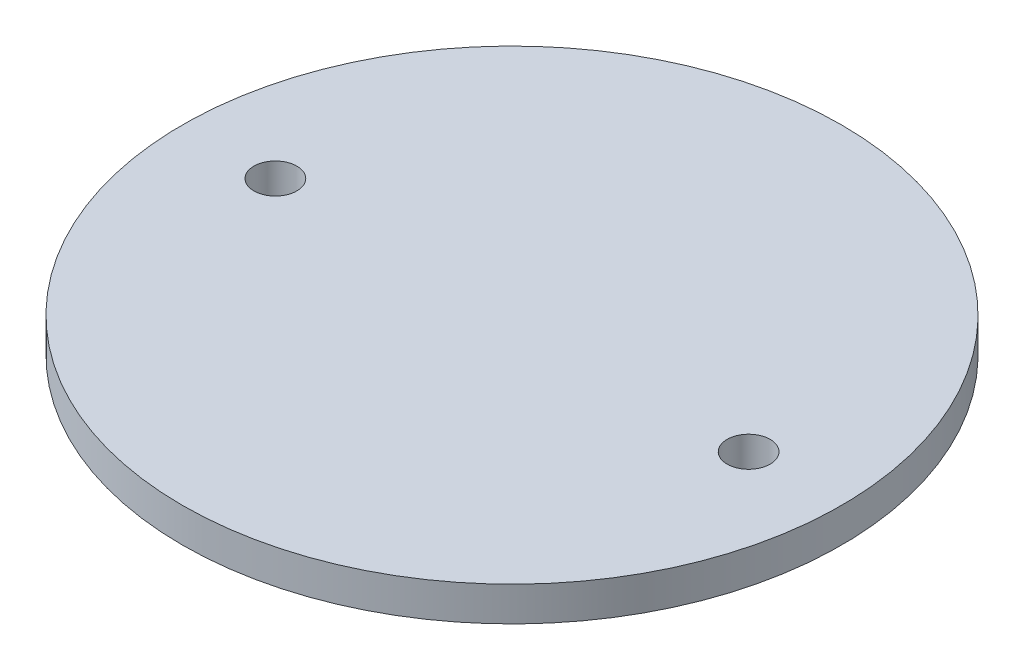
SolidWorks part; units mm, degrees
material "Balsa"
ref_plane "Front Plane" through (0, 0, 0) normal (0, 0, 1) x (1, 0, 0)
ref_plane "Top Plane" through (0, 0, 0) normal (0, 1, 0) x (1, 0, 0)
ref_plane "Right Plane" through (0, 0, 0) normal (1, 0, 0) x (0, 0, -1)
sketch "Sketch1" plane through (0, 0, 0) normal (0, 1, 0) x (1, 0, 0)
  line L0 (-38.3, 0) -> (38.3, 0) construction
  line L1 (0, 38.3) -> (0, -38.3) construction
  circle A0 centre (0, 0) radius 38.3
  circle A1 centre (-27.5, 0) radius 2.5
  circle A2 centre (27.5, 0) radius 2.5
  dimension "D1" = 55
  dimension "D2" = 76.6
  dimension "D3" = 5
extrude "Boss-Extrude1" add sketch "Sketch1" along normal blind 4
